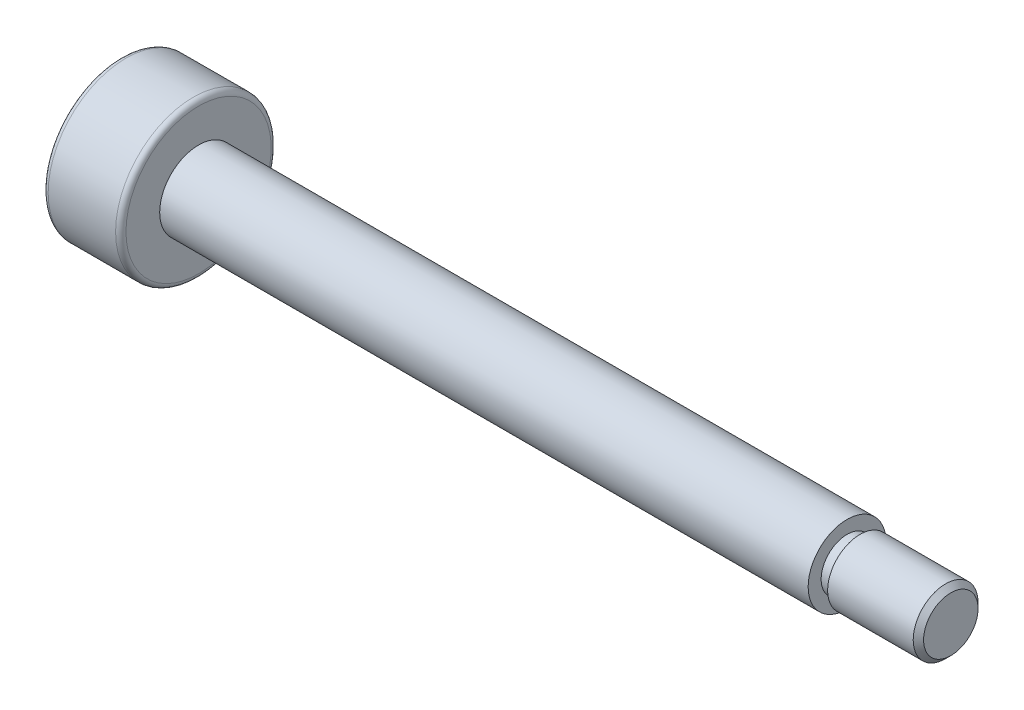
SolidWorks part; units mm, degrees
ref_plane "前视基准面" through (0, 0, 0) normal (0, 0, 1) x (1, 0, 0)
ref_plane "上视基准面" through (0, 0, 0) normal (0, 1, 0) x (1, 0, 0)
ref_plane "右视基准面" through (0, 0, 0) normal (1, 0, 0) x (0, 0, -1)
sketch "草图1" plane through (0, 0, 0) normal (0, 0, 1) x (1, 0, 0)
  line L0 (-16, 0) -> (16, 0) construction
  line L1 (-16, 0) -> (-16, 3)
  line L2 (-16, 3) -> (-13, 3)
  line L3 (-13, 3) -> (-13, 1.5)
  line L4 (-13, 1.5) -> (12, 1.5)
  line L5 (12, 1.5) -> (12, 1.25)
  line L6 (12, 1.25) -> (16, 1.25)
  line L7 (16, 1.25) -> (16, 0)
  line L8 (-16, 0) -> (16, 0)
  dimension "D1" = 3
  dimension "D2" = 6
  dimension "D3" = 2.5
  dimension "D4" = 4
  dimension "D5" = 25
  dimension "D6" = 3
revolve "旋转1" add sketch "草图1" angle 360 about L0
fillet "圆角1" radius 0.2 2 edges at (-13, 0, 3) (-16, 0, 3)
chamfer "倒角1" distance 0.2 angle 45 1 edges at (16, 0, 1.25)
sketch "草图3" plane through (0, 0, 0) normal (0, 0, 1) x (1, 0, 0)
  line L0 (12, 0) -> (15.8, 0) construction
  line L1 (12, -1.25) -> (12, 1.25) construction
  line L2 (15.8, 1.25) -> (15.8, -1.25) construction
  line L3 (12, -1.5) -> (12, 1.5) construction
  line L4 (12, 1.25) -> (12.5, 1.25)
  line L5 (12, 1.25) -> (12, 1)
  line L6 (12, 1) -> (12.5, 1)
  line L7 (12.5, 1.25) -> (12.5, 1)
  line L8 (15.8, 1.25) -> (12, 1.25) construction
  dimension "D1" = 2
  dimension "D2" = 0.5
revolve "切除-旋转1" cut sketch "草图3" angle 360 about L0
sketch "草图4" plane through (-16, 0, 0) normal (-1, 0, 0) x (0, 0, 1)
  line L1 (1.7321, 0) -> (0.866, 1.5)
  line L2 (0.866, 1.5) -> (-0.866, 1.5)
  line L3 (-0.866, 1.5) -> (-1.7321, 0)
  line L4 (-1.7321, 0) -> (-0.866, -1.5)
  line L5 (-0.866, -1.5) -> (0.866, -1.5)
  line L6 (0.866, -1.5) -> (1.7321, 0)
  circle A0 centre (0, 0) radius 1.5 construction
  dimension "D1" = 3
extrude "切除-拉伸1" cut sketch "草图4" against normal blind 2
